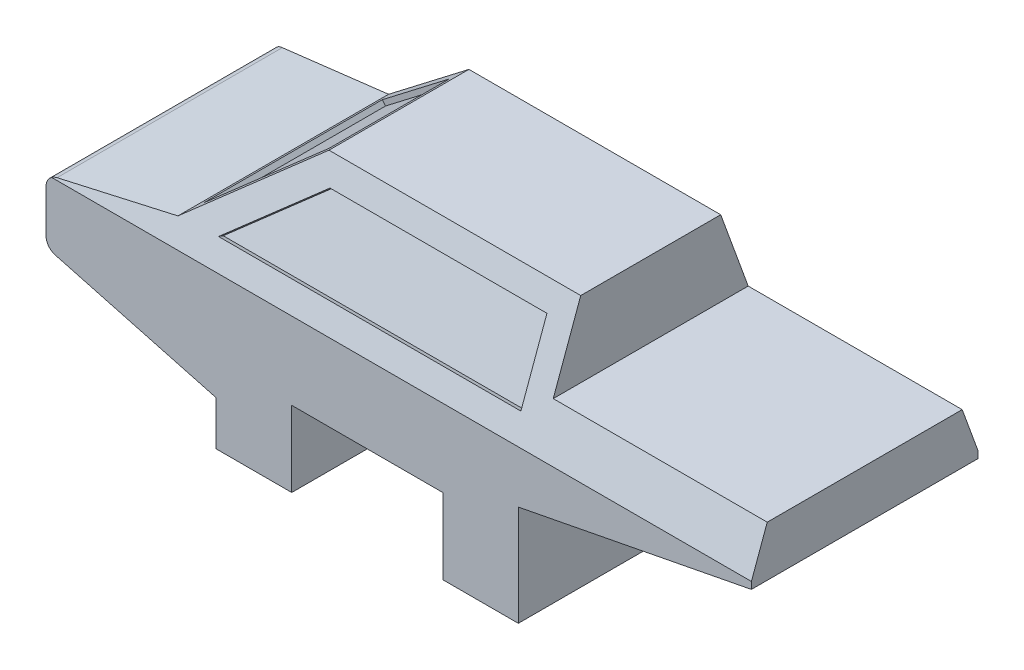
SolidWorks part; units mm, degrees
ref_plane "Front Plane" through (0, 0, 0) normal (0, 0, 1) x (1, 0, 0)
ref_plane "Top Plane" through (0, 0, 0) normal (0, 1, 0) x (1, 0, 0)
ref_plane "Right Plane" through (0, 0, 0) normal (1, 0, 0) x (0, 0, -1)
sketch "Sketch1" plane through (0, 0, 0) normal (0, 0, 1) x (1, 0, 0)
  line L0 (-125.8941, -28.7048) -> (-125.8941, -3.7048)
  line L1 (-125.8941, -3.7048) -> (-76.6537, 4.9776)
  line L2 (-76.6537, 4.9776) -> (-30.6911, 43.5449)
  line L3 (-30.6911, 43.5449) -> (69.3089, 43.5449)
  line L4 (69.3089, 43.5449) -> (69.3089, 13.5449)
  line L5 (69.3089, 13.5449) -> (154.3089, 13.5449)
  line L6 (154.3089, 13.5449) -> (154.3089, -6.4551)
  line L7 (154.3089, -6.4551) -> (61.7207, -24.411)
  line L8 (61.7207, -24.411) -> (61.7207, -64.411)
  line L9 (61.7207, -64.411) -> (31.7207, -64.411)
  line L10 (31.7207, -64.411) -> (31.7207, -34.411)
  line L11 (31.7207, -34.411) -> (-28.2793, -34.411)
  line L12 (-28.2793, -34.411) -> (-28.2793, -64.411)
  line L13 (-28.2793, -64.411) -> (-58.2793, -64.411)
  line L14 (-58.2793, -64.411) -> (-58.2793, -46.8221)
  line L15 (-58.2793, -46.8221) -> (-125.8941, -28.7048)
  dimension "D1" = 100
  dimension "D2" = 60
  dimension "D3" = 150
  dimension "D4" = 50
  dimension "D5" = 100
  dimension "D6" = 25
  dimension "D7" = 70
  dimension "D8" = 255
  dimension "D9" = 30
  dimension "D10" = 30
  dimension "D11" = 60
  dimension "D12" = 30
  dimension "D13" = 30
  dimension "D14" = 40
  dimension "D15" = 20
  dimension "D16" = 30
  dimension "D17" = 85
extrude "Boss-Extrude1" add sketch "Sketch1" against normal blind 90
sketch "Sketch2" plane through (-125.8941, 0, 0) normal (-1, 0, 0) x (0, 0, 1)
  line L0 (0, -3.7048) -> (-61.6225, 165.6016)
  line L1 (-61.6225, 165.6016) -> (0, 165.6016)
  line L2 (0, 165.6016) -> (0, -3.7048)
  line L3 (0, -3.7048) -> (0, -28.7048) construction
  line L4 (-45, -3.7048) -> (-45, 73.7807) construction
  line L5 (-90, -3.7048) -> (0, -3.7048) construction
  line L6 (-28.3775, 165.6016) -> (-90, 165.6016)
  line L7 (-90, -3.7048) -> (-28.3775, 165.6016)
  line L8 (-90, 165.6016) -> (-90, -3.7048)
  dimension "D1" = 20
  dimension "D2" = 180
extrude "Cut-Extrude1" cut sketch "Sketch2" against normal blind 337 contours L7 L0 L2 L1 | L6 L8 L7 L0
ref_plane "Plane3" through (0, -0.4334, -1.1907) normal (0, 0.342, 0.9397) x (1, 0, 0)
sketch "Sketch4" plane through (0, -0.4334, -1.1907) normal (0, 0.342, 0.9397) x (1, 0, 0)
  line L14 (-60.7884, 6.5186) -> (59.3089, 6.5186)
  line L15 (59.3089, 6.5186) -> (59.3089, 36.8007)
  line L16 (59.3089, 36.8007) -> (-26.8761, 36.8007)
  line L17 (-26.8761, 36.8007) -> (-60.7884, 6.5186)
  line L18 (-60.7884, 6.5186) -> (59.3089, 6.5186)
  line L19 (59.3089, 6.5186) -> (59.3089, 36.8007)
  line L20 (59.3089, 36.8007) -> (-26.8761, 36.8007)
  line L21 (-26.8761, 36.8007) -> (-60.7884, 6.5186)
  dimension "D1" = 10
extrude "Cut-Extrude3" cut sketch "Sketch4" against normal blind 2
ref_plane "Plane4" through (-34.1225, 40.6656, 0) normal (-0.6428, 0.766, 0) x (0.766, 0.6428, 0)
sketch "Sketch5" plane through (-34.1225, 40.6656, 0) normal (-0.6428, 0.766, 0) x (0.766, 0.6428, 0)
  line L8 (-0.5206, 68.8373) -> (-50.5206, 80.5351)
  line L9 (-50.5206, 80.5351) -> (-50.5206, 9.4649)
  line L11 (-0.5206, 21.1627) -> (-0.5206, 68.8373)
  line L13 (-50.5206, 80.5351) -> (-50.5206, 9.4649)
  line L15 (-0.5206, 21.1627) -> (-0.5206, 68.8373)
  line L16 (-0.5206, 68.8373) -> (-50.5206, 80.5351)
  line L18 (-50.5206, 9.4649) -> (-0.5206, 21.1627)
  line L19 (-50.5206, 9.4649) -> (-0.5206, 21.1627)
  dimension "D1" = 5
extrude "Cut-Extrude4" cut sketch "Sketch5" against normal blind 2
ref_plane "Plane5" through (0, 28.4921, -78.2813) normal (0, 0.342, -0.9397) x (-1, 0, 0)
sketch "Sketch7" plane through (0, 28.4921, -78.2813) normal (0, 0.342, -0.9397) x (-1, 0, 0)
  line L21 (60.7884, -24.2632) -> (26.8761, 6.0189)
  line L22 (26.8761, 6.0189) -> (-59.3089, 6.0189)
  line L23 (-59.3089, 6.0189) -> (-59.3089, -24.2632)
  line L24 (-59.3089, -24.2632) -> (60.7884, -24.2632)
  line L25 (60.7884, -24.2632) -> (26.8761, 6.0189)
  line L26 (26.8761, 6.0189) -> (-59.3089, 6.0189)
  line L27 (-59.3089, 6.0189) -> (-59.3089, -24.2632)
  line L28 (-59.3089, -24.2632) -> (60.7884, -24.2632)
  dimension "D1" = 10
extrude "Cut-Extrude5" cut sketch "Sketch7" against normal blind 2
fillet "Fillet1" radius 5 2 edges at (-125.8941, -28.7048, -45) (-125.8941, -3.7048, -45)
